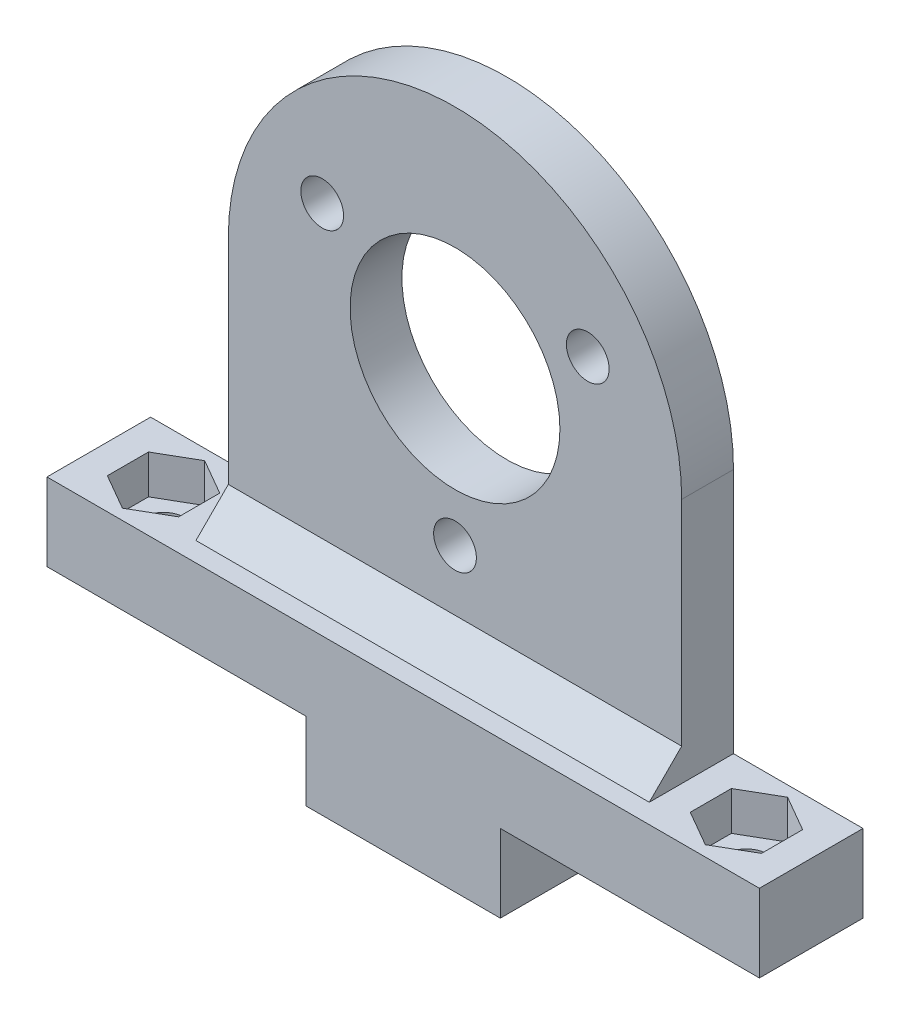
SolidWorks part; units mm, degrees
ref_plane "Plan de face" through (0, 0, 0) normal (0, 0, 1) x (1, 0, 0)
ref_plane "Plan de dessus" through (0, 0, 0) normal (0, 1, 0) x (1, 0, 0)
ref_plane "Plan de droite" through (0, 0, 0) normal (1, 0, 0) x (0, 0, -1)
sketch "Esquisse1" plane through (0, 0, 0) normal (0, 0, 1) x (1, 0, 0)
  line L0 (-27.5, -19) -> (-27.5, -25)
  line L1 (0, 0) -> (0, -30) construction
  line L2 (-17.5, 0) -> (-17.5, -19)
  line L3 (-17.5, -19) -> (-27.5, -19)
  line L4 (-27.5, -25) -> (27.5, -25) construction
  line L5 (27.5, -25) -> (27.5, -19)
  line L6 (0, -11.8357) -> (10.25, 5.9178) construction
  line L7 (10.25, 5.9178) -> (-10.25, 5.9178) construction
  line L8 (-10.25, 5.9178) -> (0, -11.8357) construction
  line L9 (17.5, 0) -> (17.5, -19)
  line L10 (17.5, -19) -> (27.5, -19)
  line L11 (-27.5, -25) -> (-7.5, -25)
  line L12 (-7.5, -25) -> (-7.5, -31)
  line L13 (-7.5, -31) -> (7.5, -31)
  line L14 (7.5, -31) -> (7.5, -25)
  line L15 (7.5, -25) -> (27.5, -25)
  circle A0 centre (0, 0) radius 17.5 construction
  arc A1 (-17.5, 0) -> (17.5, 0) centre (0, 0) cw
  circle A2 centre (0, 0) radius 8.1
  circle A3 centre (0, 0) radius 5.9178 construction
  circle A4 centre (-10.25, 5.9178) radius 1.65
  circle A5 centre (10.25, 5.9178) radius 1.65
  circle A6 centre (0, -11.8357) radius 1.65
  point P20 (0, 0)
  point P24 (0, 0)
  dimension "D1" = 35
  dimension "D5" = 60
  dimension "D6" = 60
  dimension "D8" = 3.3
  dimension "D10" = 27.5
  dimension "D2" = 55
  dimension "D3" = 6
  dimension "D4" = 25
  dimension "D7" = 20.5
  dimension "D11" = 7.5
  dimension "D12" = 15
  dimension "D13" = 6
  dimension "D9" = 3
extrude "Boss.-Extru.1" add sketch "Esquisse1" along normal blind 4
sketch "Esquisse2" plane through (0, 0, 4) normal (0, 0, 1) x (1, 0, 0)
  line L0 (-27.5, -25) -> (-7.5, -25)
  line L1 (-27.5, -25) -> (27.5, -25) construction
  line L2 (-27.5, -25) -> (-27.5, -19)
  line L3 (-27.5, -19) -> (27.5, -19)
  line L4 (27.5, -25) -> (27.5, -19)
  line L5 (-7.5, -25) -> (-7.5, -31)
  line L6 (-7.5, -31) -> (7.5, -31)
  line L7 (7.5, -31) -> (7.5, -25)
  line L8 (7.5, -25) -> (27.5, -25)
extrude "Boss.-Extru.2" add sketch "Esquisse2" along normal blind 4
chamfer "Chanfrein1" distance 2.5 angle 45 1 edges
sketch "Esquisse3" plane through (0, -19, 0) normal (0, 1, 0) x (1, 0, 0)
  line L0 (0, 0) -> (0, -8) construction
  line L2 (27.5, -8) -> (-27.5, -8) construction
  line L5 (-27.5, -4) -> (27.5, -4) construction
  line L6 (-27.5, -8) -> (-27.5, 0) construction
  line L7 (27.5, -8) -> (27.5, 0) construction
  line L8 (19.75, -2.4123) -> (22.5, -0.8246)
  line L9 (-22.5, -0.8246) -> (-25.25, -2.4123)
  line L10 (-25.25, -2.4123) -> (-25.25, -5.5877)
  line L11 (-25.25, -5.5877) -> (-22.5, -7.1754)
  line L12 (-22.5, -7.1754) -> (-19.75, -5.5877)
  line L13 (-19.75, -5.5877) -> (-19.75, -2.4123)
  line L14 (-19.75, -2.4123) -> (-22.5, -0.8246)
  line L15 (19.75, -5.5877) -> (19.75, -2.4123)
  line L16 (22.5, -7.1754) -> (19.75, -5.5877)
  line L17 (25.25, -5.5877) -> (22.5, -7.1754)
  line L18 (25.25, -2.4123) -> (25.25, -5.5877)
  line L19 (22.5, -0.8246) -> (25.25, -2.4123)
  circle A0 centre (-22.5, -4) radius 2.75 construction
  circle A1 centre (22.5, -4) radius 2.75 construction
  dimension "D1" = 22.5
extrude "Enlèv. mat.-Extru.1" cut sketch "Esquisse3" against normal blind 3
sketch "Esquisse5" plane through (0, -19, 0) normal (0, 1, 0) x (1, 0, 0)
  line L0 (-27.5, -4) -> (27.5, -4) construction
  line L1 (-27.5, -8) -> (-27.5, 0) construction
  line L2 (27.5, -8) -> (27.5, 0) construction
  line L3 (0, 0) -> (0, -8) construction
  line L6 (27.5, -8) -> (-27.5, -8) construction
  circle A0 centre (-22.5, -4) radius 1.6
  circle A1 centre (22.5, -4) radius 1.6
  dimension "D1" = 22.5
extrude "Enlèv. mat.-Extru.2" cut sketch "Esquisse5" against normal through all
